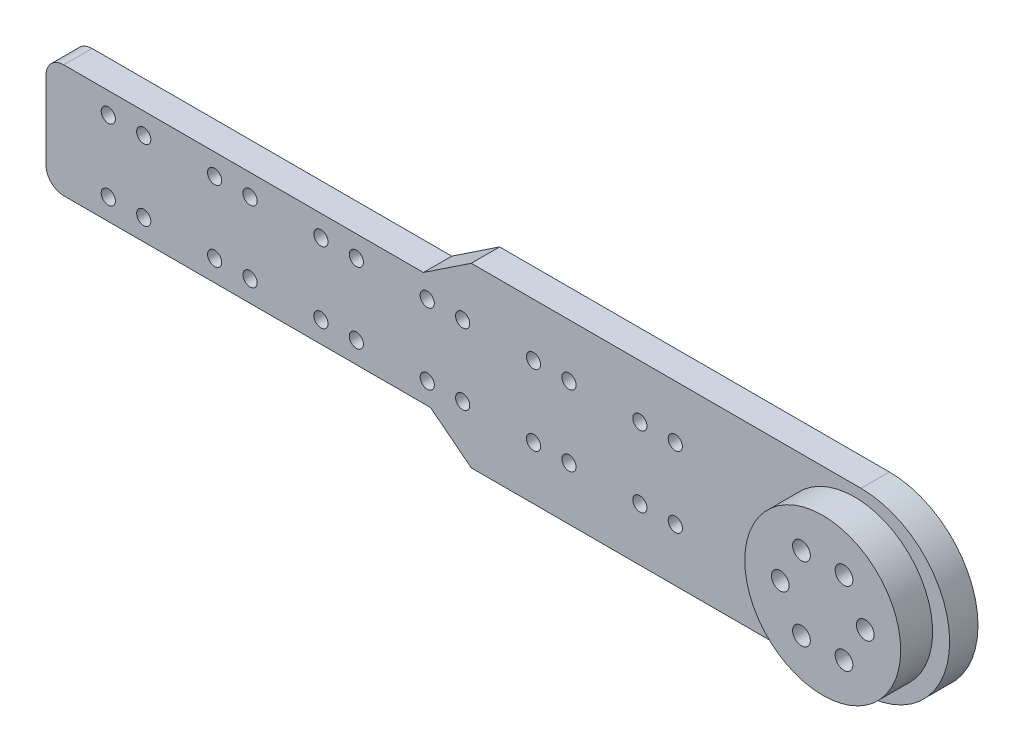
SolidWorks part; units mm, degrees
ref_plane "前视基准面" through (0, 0, 0) normal (0, 0, 1) x (1, 0, 0)
ref_plane "上视基准面" through (0, 0, 0) normal (0, 1, 0) x (1, 0, 0)
ref_plane "右视基准面" through (0, 0, 0) normal (1, 0, 0) x (0, 0, -1)
sketch "草图1" plane through (0, 0, 0) normal (0, 0, 1) x (1, 0, 0)
  line L0 (0, 0) -> (-115, 0) construction
  line L1 (-115, -25) -> (115, -25)
  line L2 (-115, -25) -> (-115, 25)
  line L3 (-115, 25) -> (115, 25)
  line L5 (-115, -25) -> (115, 25) construction
  line L6 (-115, 25) -> (115, -25) construction
  arc A0 (115, 25) -> (115, -25) centre (115, 0) cw
  circle A1 centre (-67.4223, 10) radius 2
  circle A2 centre (-67.4223, -10) radius 2
  circle A3 centre (-57.4223, 10) radius 2
  circle A4 centre (-57.4223, -10) radius 2
  circle A5 centre (-37.4223, 10) radius 2
  circle A6 centre (-27.4223, 10) radius 2
  circle A7 centre (-37.4223, -10) radius 2
  circle A8 centre (-27.4223, -10) radius 2
  circle A9 centre (-7.4223, 10) radius 2
  circle A10 centre (2.5777, 10) radius 2
  circle A11 centre (-7.4223, -10) radius 2
  circle A12 centre (2.5777, -10) radius 2
  circle A13 centre (22.5777, 10) radius 2
  circle A14 centre (32.5777, 10) radius 2
  circle A15 centre (22.5777, -10) radius 2
  circle A16 centre (32.5777, -10) radius 2
  circle A17 centre (-97.4223, 10) radius 2
  circle A18 centre (-97.4223, -10) radius 2
  circle A19 centre (-87.4223, 10) radius 2
  circle A20 centre (-87.4223, -10) radius 2
  circle A21 centre (52.5777, 10) radius 2
  circle A22 centre (62.5777, 10) radius 2
  circle A23 centre (52.5777, -10) radius 2
  circle A24 centre (62.5777, -10) radius 2
  point P0 (0, 0)
  dimension "D3" = 25
  dimension "D4" = 4
  dimension "D1" = 230
  dimension "D2" = 50
  dimension "D5" = 10
  dimension "D6" = 2
  dimension "D7" = 4
  dimension "D8" = 30
  dimension "D9" = 2
  dimension "D10" = 2
extrude "凸台-拉伸1" add sketch "草图1" along normal blind 8
fillet "圆角1" radius 10 2 edges at (-115, -25, 4) (-115, 25, 4)
sketch "草图2" plane through (0, 0, 8) normal (0, 0, 1) x (1, 0, 0)
  line L10 (115, 25) -> (-105, 25) construction
  line L20 (101.1849, 0) -> (107.1849, -10.3923) construction
  line L21 (107.1849, -10.3923) -> (119.1849, -10.3923) construction
  line L22 (119.1849, -10.3923) -> (125.1849, 0) construction
  line L23 (125.1849, 0) -> (119.1849, 10.3923) construction
  line L24 (119.1849, 10.3923) -> (107.1849, 10.3923) construction
  line L25 (107.1849, 10.3923) -> (101.1849, 0) construction
  circle A0 centre (113.1849, 0) radius 22
  circle A1 centre (113.1849, 0) radius 12 construction
  circle A3 centre (119.1849, -10.3923) radius 2.5
  circle A4 centre (107.1849, -10.3923) radius 2.5
  circle A5 centre (101.1849, 0) radius 2.5
  circle A6 centre (107.1849, 10.3923) radius 2.5
  circle A7 centre (119.1849, 10.3923) radius 2.5
  circle A8 centre (125.1849, 0) radius 2.5
  dimension "D1" = 44
  dimension "D3" = 5
  dimension "D2" = 25
  dimension "D4" = 12
extrude "凸台-拉伸3" add sketch "草图2" along normal blind 9
hole_wizard "大小mm 暗销孔1" positions "草图5" profile "草图6" hole size "Ø5.0" standard "GB" end condition through all
sketch "草图5" plane through (0, 0, 8) normal (0, 0, 1) x (1, 0, 0)
  point P0 (119.1849, -10.3923)
  point P3 (107.1849, -10.3923)
  point P6 (101.1849, 0)
  point P9 (107.1849, 10.3923)
  point P12 (119.1849, 10.3923)
  point P16 (125.1849, 0)
sketch "草图6" plane through (119.1849, -10.3923, 8) normal (1, 0, 0) x (0, -1, 0)
  line L0 (0, 0) -> (0, 8)
  line L1 (0, 8) -> (2.5, 8)
  line L2 (2.5, 8) -> (2.5, 0)
  line L5 (2.5, 0) -> (0, 0)
  line L11 (0, -6.35) -> (0, 107.95) construction
  dimension "通孔孔直径" = 5
  dimension "通孔孔深度" = 8
sketch "草图11" plane through (0, 0, 8) normal (0, 0, 1) x (1, 0, 0)
  line L0 (5, 25) -> (5, 16)
  line L1 (115, 25) -> (-105, 25) construction
  line L2 (5, 16) -> (-115, 16)
  line L3 (-115, 15) -> (-115, -15) construction
  line L4 (0, 0) -> (-115, 0) construction
  line L5 (5, -25) -> (5, -16)
  line L6 (5, -16) -> (-115, -16)
  line L7 (-115, 16) -> (-115, 25)
  line L8 (-115, 25) -> (5, 25)
  line L9 (-115, -16) -> (-115, -25)
  line L10 (-115, -25) -> (5, -25)
  dimension "D1" = 32
extrude "切除-拉伸2" cut sketch "草图11" against normal through all
fillet "圆角5" radius 5 1 edges at (-114.9499, 16, 4)
fillet "圆角8" radius 5 1 edges at (-114.9499, -16, 4)
sketch "草图14" plane through (0, 0, 0) normal (0, 0, -1) x (-1, 0, 0)
  line L0 (-5, 25) -> (8.5021, 16)
  line L1 (110, 16) -> (-5, 16) construction
rib "筋9" sketch "草图14" sketch "草图14" thickness 8 extrusion direction parallel to sketch draft on no parameters "D1"=8
sketch "草图16" plane through (0, 0, 8) normal (0, 0, 1) x (1, 0, 0)
  line L0 (5, -25) -> (-6.5054, -16)
  line L1 (5, -16) -> (-110, -16) construction
rib "筋26" sketch "草图16" sketch "草图16" thickness 8 extrusion direction parallel to sketch draft on no parameters "D1"=8
